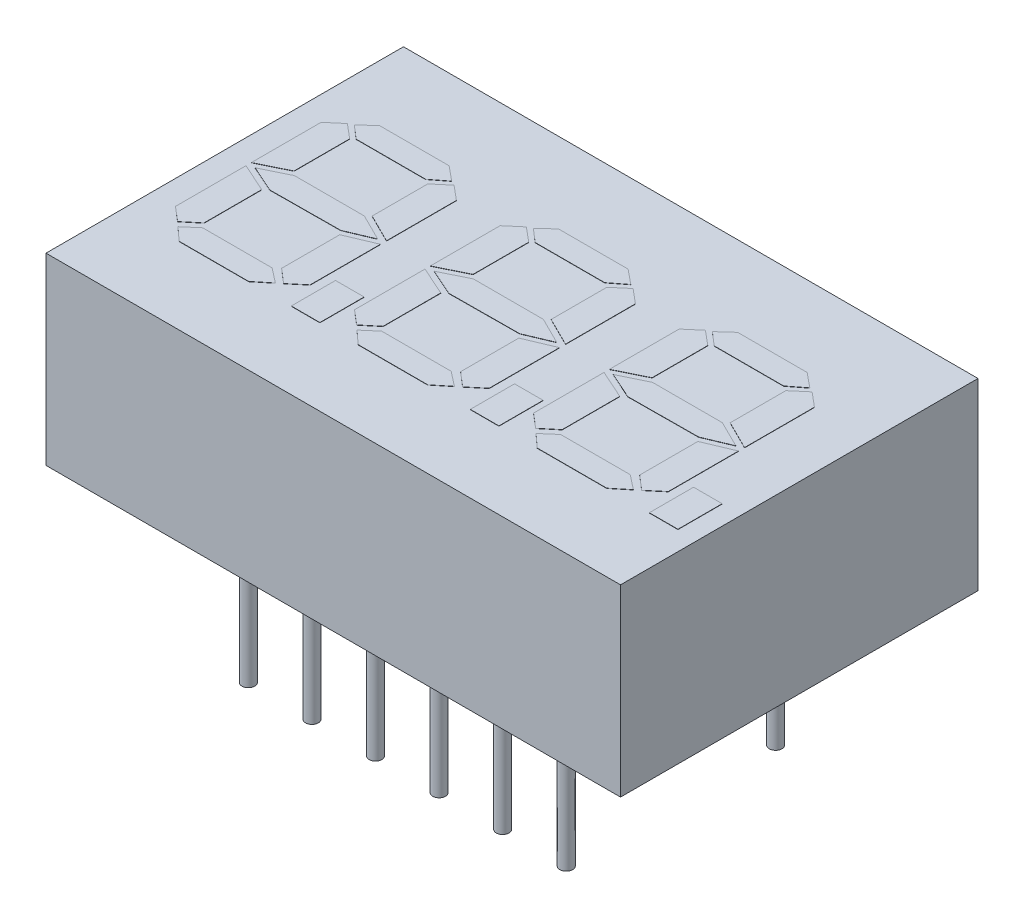
SolidWorks part; units mm, degrees
ref_plane "前视基准面" through (0, 0, 0) normal (0, 0, 1) x (1, 0, 0)
ref_plane "上视基准面" through (0, 0, 0) normal (0, 1, 0) x (1, 0, 0)
ref_plane "右视基准面" through (0, 0, 0) normal (1, 0, 0) x (0, 0, -1)
sketch "草图1" plane through (0, 0, 0) normal (0, 1, 0) x (1, 0, 0)
  line L0 (-29.3463, 0) -> (31.8739, 0) construction
  line L1 (-11.25, 7) -> (11.25, 7)
  line L2 (-11.25, 7) -> (-11.25, -7)
  line L3 (-11.25, -7) -> (11.25, -7)
  line L4 (11.25, 7) -> (11.25, -7)
  line L5 (0, 30.3794) -> (0, -29.5342) construction
  dimension "D1" = 22.5
  dimension "D2" = 14
extrude "拉伸1" add sketch "草图1" along normal blind 7.2
sketch "草图2" plane through (0, 0, 0) normal (0, -1, 0) x (1, 0, 0)
  line L0 (22.7617, 0) -> (-24.809, 0) construction
  line L1 (0, 10.3572) -> (0, -11.9228) construction
  line L2 (5.6198, 4.1) -> (-6.2174, 4.1) construction
  line L3 (5.6198, -4.1) -> (-6.2174, -4.1) construction
  circle A0 centre (6.2247, 4.1) radius 0.25
  circle A1 centre (3.7348, 4.1) radius 0.25
  circle A2 centre (1.2449, 4.1) radius 0.25
  circle A3 centre (-1.2449, 4.1) radius 0.25
  circle A4 centre (-3.7348, 4.1) radius 0.25
  circle A5 centre (-6.2247, 4.1) radius 0.25
  circle A6 centre (-6.2247, -4.1) radius 0.25
  circle A7 centre (-3.7348, -4.1) radius 0.25
  circle A8 centre (-1.2449, -4.1) radius 0.25
  circle A9 centre (1.2449, -4.1) radius 0.25
  circle A10 centre (3.7348, -4.1) radius 0.25
  circle A11 centre (6.2247, -4.1) radius 0.25
  dimension "D1" = 0.5
  dimension "D2" = 8.2
extrude "拉伸2" add sketch "草图2" along normal blind 6.3
sketch "草图3" plane through (0, 7.2, 0) normal (0, 1, 0) x (1, 0, 0)
  text T0 "8.8.8." font "DigifaceWide" height 8
  dimension "D1" = 10.8
  dimension "D2" = 4
extrude "凸台-拉伸1" add sketch "草图3" along normal blind 0.01
